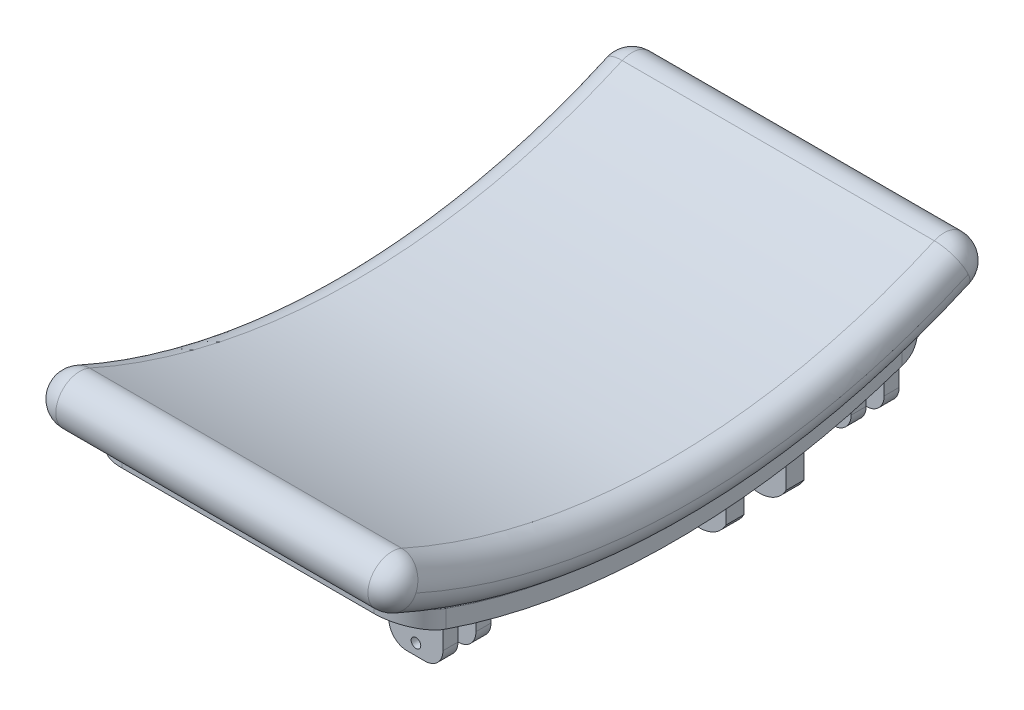
SolidWorks part; units mm, degrees
ref_plane "Front Plane" through (0, 0, 0) normal (0, 0, 1) x (1, 0, 0)
ref_plane "Top Plane" through (0, 0, 0) normal (0, 1, 0) x (1, 0, 0)
ref_plane "Right Plane" through (0, 0, 0) normal (1, 0, 0) x (0, 0, -1)
sketch "Sketch1" plane through (0, 0, 0) normal (1, 0, 0) x (0, 0, -1)
  line L0 (0, 0) -> (0, -453.7937) construction
  line L1 (-230, -404.6702) -> (0, 0) construction
  line L2 (0, 0) -> (230, -404.6702) construction
  line L3 (-230, -404.6702) -> (230, -404.6702) construction
  arc A0 (-230, -404.6702) -> (230, -404.6702) centre (0, 109.2063) ccw construction
  arc A1 (-238.1705, -422.9251) -> (238.1705, -422.9251) centre (0, 109.2063) ccw
  arc A2 (-221.8295, -386.4152) -> (221.8295, -386.4152) centre (0, 109.2063) ccw
  arc A3 (-221.8295, -386.4152) -> (-238.1705, -422.9251) centre (-230, -404.6702) ccw
  arc A4 (238.1705, -422.9251) -> (221.8295, -386.4152) centre (230, -404.6702) ccw
  point P3 (0, -453.7937)
  dimension "D1" = 40
  dimension "D2" = 543
  dimension "D3" = 460
  dimension "D4" = 29.612
extrude "Boss-Extrude1" add sketch "Sketch1" along normal mid plane 300
fillet "Fillet1" radius 20 8 edges at (-150, -396.4997, -248.2549) (-150, -473.7937, 0) (-150, -396.4997, 248.2549) (150, -396.4997, -248.2549) (150, -473.7937, 0) (150, -396.4997, 248.2549) (-150, -433.7937, 0) (150, -433.7937, 0)
sketch "Sketch2" plane through (0, 0, 0) normal (1, 0, 0) x (0, 0, -1)
  line L2 (-220, -430.6909) -> (-220, -446.9125)
  line L3 (220, -430.6909) -> (220, -446.9125)
  arc A0 (-220, -430.6909) -> (220, -430.6909) centre (0, 95.6109) ccw
  arc A1 (-238.1705, -422.9251) -> (238.1705, -422.9251) centre (0, 109.2063) ccw construction
  arc A2 (-220, -446.9125) -> (220, -446.9125) centre (0, 95.6109) ccw
  arc A3 (-225.7851, -444.5305) -> (225.7851, -444.5305) centre (0, 95.6109) ccw construction
  point P10 (0, -474.8219)
  dimension "D3" = 585.4328
  dimension "D2" = 220
  dimension "D1" = 15
extrude "Boss-Extrude2" add sketch "Sketch2" along normal mid plane 270 separate body
fillet "Fillet2" radius 30 4 edges at (135, -438.8017, -220) (-135, -438.8017, -220) (-135, -438.8017, 220) (135, -438.8017, 220)
ref_plane "Plane1" through (0, -490, 0) normal (0, 1, 0) x (1, 0, 0)
sketch "Sketch3" plane through (0, -490, 0) normal (0, 1, 0) x (1, 0, 0)
  line L1 (87.5, -190) -> (132.5, -190)
  line L2 (87.5, -190) -> (87.5, -150)
  line L3 (87.5, -150) -> (132.5, -150)
  line L4 (132.5, -190) -> (132.5, -150)
  line L5 (87.5, -190) -> (132.5, -150) construction
  line L6 (87.5, -150) -> (132.5, -190) construction
  line L7 (87.5, 150) -> (132.5, 150)
  line L8 (87.5, 150) -> (87.5, 190)
  line L9 (87.5, 190) -> (132.5, 190)
  line L10 (132.5, 150) -> (132.5, 190)
  line L11 (87.5, 150) -> (132.5, 190) construction
  line L12 (87.5, 190) -> (132.5, 150) construction
  point P0 (110, -170)
  point P5 (110, 170)
  dimension "D1" = 170
  dimension "D2" = 170
  dimension "D3" = 110
  dimension "D4" = 110
  dimension "D5" = 45
  dimension "D6" = 40
  dimension "D7" = 45
  dimension "D8" = 40
extrude "Boss-Extrude3" add sketch "Sketch3" along normal up to next
sketch "Sketch4" plane through (0, 0, -190) normal (0, 0, -1) x (-1, 0, 0)
  arc A1 (-132.5, -458.1324) -> (-87.5, -458.1324) centre (-110, -458.1324) ccw
sketch "Sketch5" plane through (0, -490, 0) normal (0, -1, 0) x (1, 0, 0)
  line L0 (87.5, -150) -> (132.5, -190) construction
  line L1 (132.5, -190) -> (132.5, -150) construction
  line L2 (87.5, -162.5) -> (132.5, -162.5)
  line L3 (87.5, -162.5) -> (87.5, -177.5)
  line L4 (87.5, -177.5) -> (132.5, -177.5)
  line L5 (132.5, -162.5) -> (132.5, -177.5)
  line L6 (87.5, -162.5) -> (132.5, -177.5) construction
  line L7 (87.5, -177.5) -> (132.5, -162.5) construction
  point P4 (110, -170)
  dimension "D1" = 15
extrude "Cut-Extrude1" cut sketch "Sketch5" against normal blind 30
mirror "Mirror1" about plane through (0, 0, 0) normal (0, 0, 1) of "Cut-Extrude1"
fillet "Fillet3" radius 15 8 edges at (87.5, -490, 156.25) (87.5, -490, 183.75) (132.5, -490, 183.75) (132.5, -490, 156.25) (87.5, -490, -156.25) (132.5, -490, -156.25) (87.5, -490, -183.75) (132.5, -490, -183.75)
sketch "Sketch6" plane through (0, 0, 190) normal (0, 0, 1) x (1, 0, 0)
  circle A0 centre (110, -480.6324) radius 4
  arc A1 (87.5, -458.1324) -> (132.5, -458.1324) centre (110, -458.1324) ccw construction
  dimension "D1" = 8
extrude "Cut-Extrude2" cut sketch "Sketch6" against normal blind 44
mirror "Mirror2" about plane through (0, 0, 0) normal (0, 0, 1) of "Cut-Extrude2"
ref_plane "Plane2" through (0, -530, 0) normal (0, 1, 0) x (1, 0, 0)
sketch "Sketch7" plane through (0, -530, 0) normal (0, 1, 0) x (1, 0, 0)
  line L0 (38.9196, 91.25) -> (135, 91.25) construction
  line L2 (119.4598, 73.75) -> (119.4598, 58.75)
  line L3 (119.4598, 123.75) -> (54.4598, 123.75)
  line L4 (119.4598, 123.75) -> (119.4598, 108.75)
  line L5 (119.4598, 58.75) -> (54.4598, 58.75)
  line L6 (54.4598, 123.75) -> (54.4598, 108.75)
  line L7 (119.4598, 123.75) -> (54.4598, 58.75) construction
  line L8 (119.4598, 58.75) -> (54.4598, 123.75) construction
  line L9 (119.4598, 108.75) -> (54.4598, 108.75)
  line L11 (119.4598, 73.75) -> (54.4598, 73.75)
  line L13 (119.4598, 108.75) -> (54.4598, 73.75) construction
  line L14 (119.4598, 73.75) -> (54.4598, 108.75) construction
  line L15 (54.4598, 73.75) -> (54.4598, 58.75)
  point P5 (86.9598, 91.25)
  point P10 (86.9598, 91.25)
  dimension "D1" = 65
  dimension "D2" = 65
  dimension "D3" = 35
  dimension "D4" = 91.25
extrude "Boss-Extrude4" add sketch "Sketch7" along normal up to next
sketch "Sketch8" [suppressed] plane through (0, 0, 32.5) normal (0, 0, 1) x (1, 0, 0)
  line L0 (105, -488.9191) -> (105, -530) construction
  line L2 (67.2626, -524.2111) -> (40, -488.9191)
  line L3 (40, -488.9191) -> (40, -530)
  line L4 (105, -513.5075) -> (105, -530)
  line L5 (105, -530) -> (40, -530)
  arc A0 (105, -513.5075) -> (67.2626, -524.2111) centre (83.9852, -511.2931) cw
  circle A1 centre (83.9852, -511.2931) radius 4
  dimension "D1" = 8
extrude "Cut-Extrude3" [suppressed] cut sketch "Sketch8" against normal through all
fillet "Fillet4" radius 1 8 edges at (127.6126, -434.8732, -209.7147) (0, -430.6909, -220) (-122.6954, -433.0677, -214.2254) (-135, -474.8219, 0) (-127.6126, -434.8732, 209.7147) (0, -430.6909, 220) (122.6954, -433.0677, 214.2254) (135, -474.8219, 0)
sketch "Sketch9" plane through (0, 0, -123.75) normal (0, 0, -1) x (-1, 0, 0)
  line L0 (-54.4598, -476.5932) -> (-75.4954, -515.2293)
  line L1 (-119.4598, -476.5932) -> (-119.4598, -530) construction
  line L2 (-54.4598, -476.5932) -> (-54.4598, -530)
  line L3 (-54.4598, -530) -> (-119.4598, -530)
  line L4 (-119.4598, -530) -> (-119.4598, -515.2293)
  arc A0 (-75.4954, -515.2293) -> (-119.4598, -515.2293) centre (-97.4776, -503.261) cw
  circle A1 centre (-97.4776, -503.261) radius 3
  dimension "D1" = 6
extrude "Cut-Extrude5" cut sketch "Sketch9" against normal up to surface (65 mm away) up to face at (86.9598, -508.4333, -58.75)
